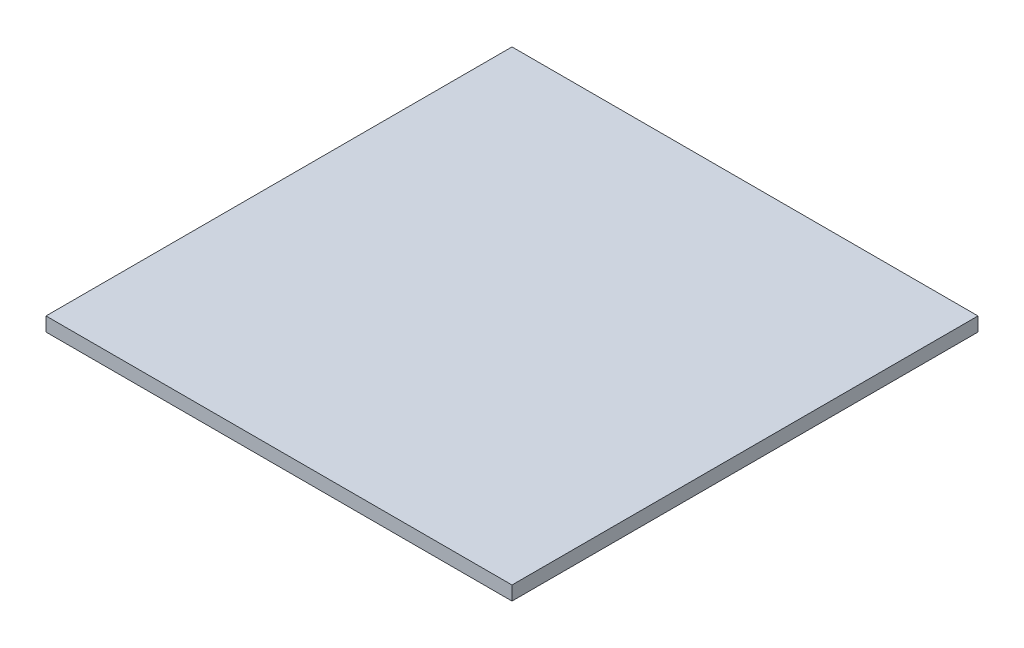
SolidWorks part; units mm, degrees
ref_plane "Front Plane" through (0, 0, 0) normal (0, 0, 1) x (1, 0, 0)
ref_plane "Top Plane" through (0, 0, 0) normal (0, 1, 0) x (1, 0, 0)
ref_plane "Right Plane" through (0, 0, 0) normal (1, 0, 0) x (0, 0, -1)
sketch "Sketch2" plane through (0, 0, 0) normal (0, 1, 0) x (1, 0, 0)
  line L1 (-25.4, 25.4) -> (25.4, 25.4)
  line L2 (-25.4, 25.4) -> (-25.4, -25.4)
  line L3 (-25.4, -25.4) -> (25.4, -25.4)
  line L4 (25.4, 25.4) -> (25.4, -25.4)
  line L5 (-25.4, 25.4) -> (25.4, -25.4) construction
  line L6 (-25.4, -25.4) -> (25.4, 25.4) construction
  point P0 (0, 0)
  dimension "D1" = 50.8
  dimension "D2" = 50.8
extrude "Boss-Extrude1" add sketch "Sketch2" along normal blind 1.524
